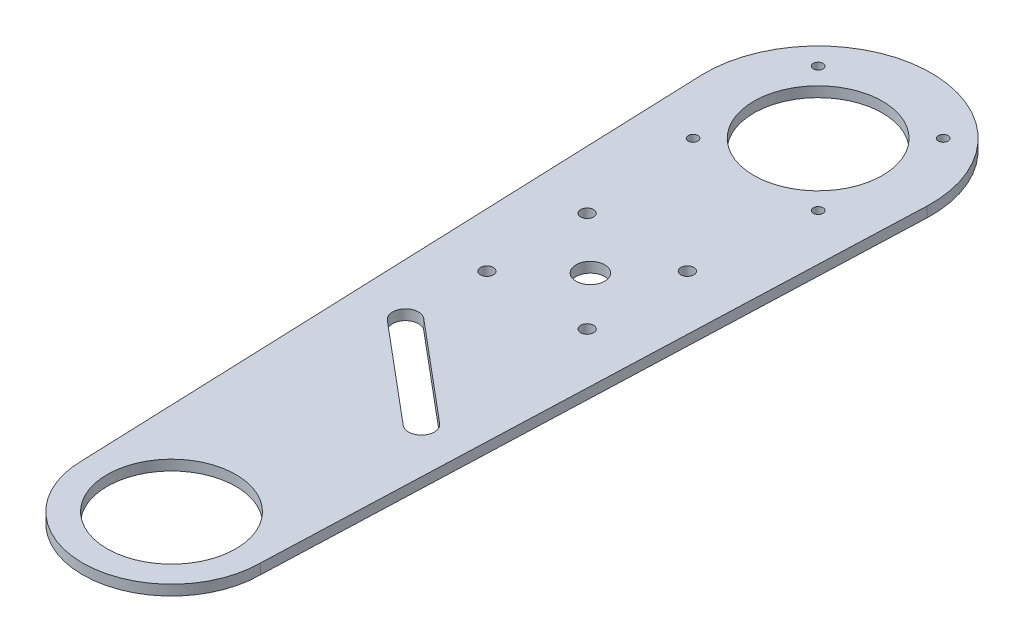
SolidWorks part; units mm, degrees
ref_plane "Front Plane" through (0, 0, 0) normal (0, 0, 1) x (1, 0, 0)
ref_plane "Top Plane" through (0, 0, 0) normal (0, 1, 0) x (1, 0, 0)
ref_plane "Right Plane" through (0, 0, 0) normal (1, 0, 0) x (0, 0, -1)
sketch "Sketch1" plane through (0, 0, 0) normal (0, 1, 0) x (1, 0, 0)
  line L0 (-27.5, -100) -> (-34.9753, 98.6841)
  line L1 (27.5, -100) -> (34.9753, 98.6841)
  arc A0 (-27.5, -100) -> (27.5, -100) centre (0, -100) ccw
  arc A2 (34.9753, 98.6841) -> (-34.9753, 98.6841) centre (0, 100) ccw
  dimension "D1" = 55
  dimension "D2" = 200
  dimension "D3" = 70
  dimension "D4" = 100
extrude "Boss-Extrude1" add sketch "Sketch1" along normal blind 3.175
sketch "Sketch2" plane through (0, 3.175, 0) normal (0, 1, 0) x (1, 0, 0)
  circle A0 centre (0, -100) radius 19.9
  circle A1 centre (0, 100) radius 19.9
  dimension "D1" = 39.8
  dimension "D2" = 200
  dimension "D3" = 100
extrude "Cut-Extrude1" cut sketch "Sketch2" against normal through all
sketch "Esquisse1" plane through (0, 3.175, 0) normal (0, 1, 0) x (1, 0, 0)
  circle A0 centre (0, 100) radius 27.35
  circle A2 centre (0, 100) radius 19.9 construction
  dimension "D1" = 54.7
sketch "Esquisse2" plane through (0, 3.175, 0) normal (0, 1, 0) x (1, 0, 0)
  line L0 (-19.3394, 80.6606) -> (19.3394, 80.6606) construction
  line L1 (19.3394, 80.6606) -> (19.3394, 119.3394) construction
  line L2 (19.3394, 119.3394) -> (-19.3394, 119.3394) construction
  line L3 (-19.3394, 119.3394) -> (-19.3394, 80.6606) construction
  circle A0 centre (19.3394, 80.6606) radius 1.5
  circle A2 centre (19.3394, 119.3394) radius 1.5
  circle A3 centre (-19.3394, 119.3394) radius 1.5
  circle A4 centre (-19.3394, 80.6606) radius 1.5
  circle A6 centre (0, 100) radius 27.35 construction
  point P2 (0, 80.6606)
  dimension "D1" = 3
extrude "Enlèv. mat.-Extru.1" cut sketch "Esquisse2" against normal through all
sketch "Sketch3" plane through (0, 3.175, 0) normal (0, 1, 0) x (1, 0, 0)
  circle A0 centre (0.85, 28.7) radius 4.425
  dimension "D1" = 8.85
extrude "Cut-Extrude2" cut sketch "Sketch3" against normal through all
sketch "Sketch5" plane through (0, 3.175, 0) normal (0, 1, 0) x (1, 0, 0)
  line L3 (12.7497, -41.0757) -> (-17.892, -15.3642)
  line L4 (-12.7497, -9.2358) -> (17.892, -34.9473)
  arc A2 (-17.892, -15.3642) -> (-12.7497, -9.2358) centre (-15.3209, -12.3) cw
  arc A3 (17.892, -34.9473) -> (12.7497, -41.0757) centre (15.3209, -38.0115) cw
extrude "Cut-Extrude4" cut sketch "Sketch5" against normal through all
sketch "Sketch6" plane through (0, 0, 0) normal (0, -1, 0) x (-1, 0, 0)
  circle A5 centre (-15.35, 13.2) radius 2
  circle A6 centre (-15.35, 44.2) radius 2
  circle A7 centre (15.65, 44.2) radius 2
  circle A8 centre (15.65, 13.2) radius 2
  dimension "D1" = 4
extrude "Cut-Extrude5" cut sketch "Sketch6" against normal through all
